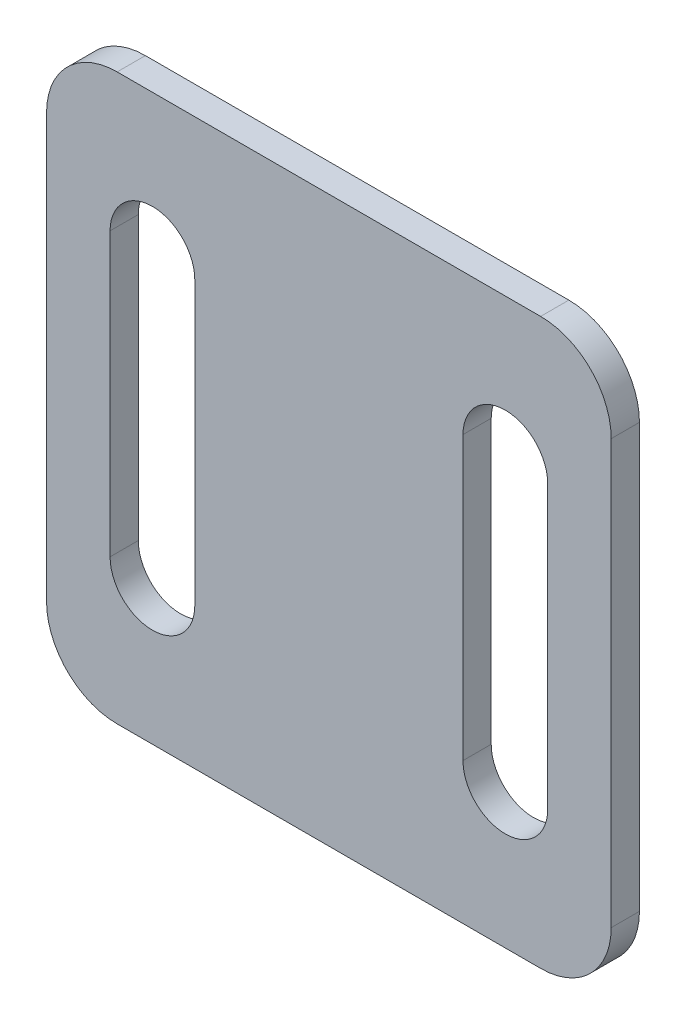
SolidWorks part; units mm, degrees
material "AISI 304"
ref_plane "Спереди" through (0, 0, 0) normal (0, 0, 1) x (1, 0, 0)
ref_plane "Сверху" through (0, 0, 0) normal (0, 1, 0) x (1, 0, 0)
ref_plane "Справа" through (0, 0, 0) normal (1, 0, 0) x (0, 0, -1)
other "Configuration Table"
sketch "Эскиз1" plane through (0, 0, 0) normal (0, 0, 1) x (1, 0, 0)
  line L0 (-25, 0) -> (25, 0) construction
  line L1 (-40, -40) -> (40, -40)
  line L2 (-40, -40) -> (-40, 40)
  line L3 (-40, 40) -> (40, 40)
  line L4 (40, -40) -> (40, 40)
  line L5 (-40, -40) -> (40, 40) construction
  line L6 (-40, 40) -> (40, -40) construction
  line L7 (25, -20) -> (25, 20) construction
  line L8 (19, -20) -> (19, 20)
  line L9 (31, -20) -> (31, 20)
  line L10 (-25, -20) -> (-25, 20) construction
  line L11 (-31, -20) -> (-31, 20)
  line L12 (-19, -20) -> (-19, 20)
  arc A1 (19, -20) -> (31, -20) centre (25, -20) ccw
  arc A2 (31, 20) -> (19, 20) centre (25, 20) ccw
  arc A3 (-31, -20) -> (-19, -20) centre (-25, -20) ccw
  arc A4 (-19, 20) -> (-31, 20) centre (-25, 20) ccw
  point P0 (0, 0)
  point P9 (0, 0)
  point P11 (25, 0)
  point P18 (-25, 0)
  dimension "D3" = 40
  dimension "D1" = 80
  dimension "D2" = 80
  dimension "D4" = 12
  dimension "D5" = 50
extrude "Бобышка-Вытянуть1" add sketch "Эскиз1" along normal blind 4
fillet "Скругление1" radius 10 4 edges at (40, 40, 2) (40, -40, 2) (-40, -40, 2) (-40, 40, 2)
